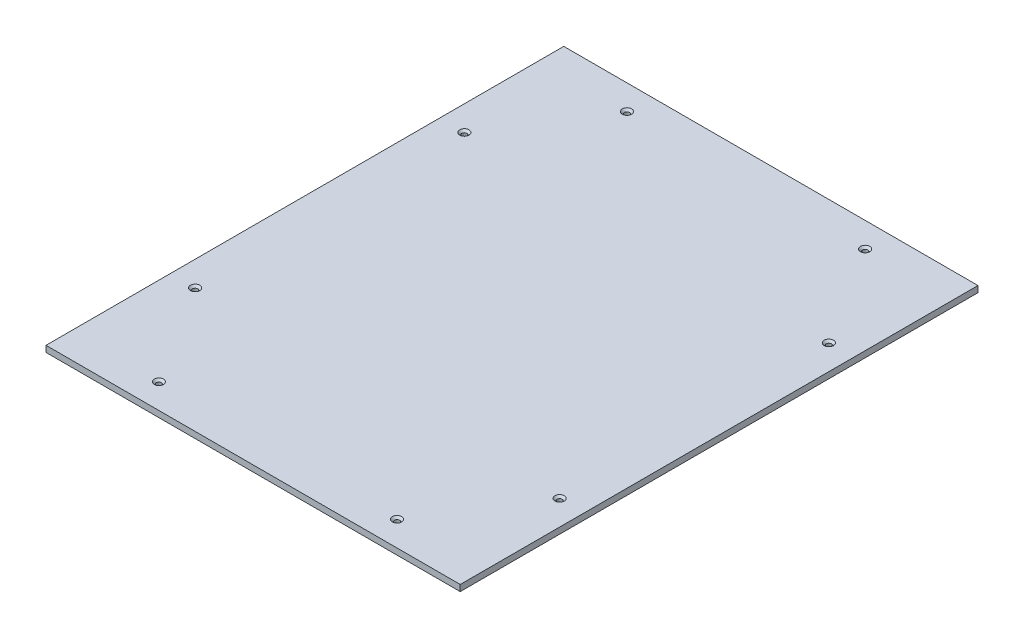
SolidWorks part; units mm, degrees
ref_plane "Plan de face" through (0, 0, 0) normal (0, 0, 1) x (1, 0, 0)
ref_plane "Plan de dessus" through (0, 0, 0) normal (0, 1, 0) x (1, 0, 0)
ref_plane "Plan de droite" through (0, 0, 0) normal (1, 0, 0) x (0, 0, -1)
sketch "Esquisse1" plane through (0, 0, 0) normal (0, 1, 0) x (1, 0, 0)
  line L1 (-200, -250) -> (200, -250)
  line L2 (-200, -250) -> (-200, 250)
  line L3 (-200, 250) -> (200, 250)
  line L4 (200, -250) -> (200, 250)
  line L5 (-200, -250) -> (200, 250) construction
  line L6 (-200, 250) -> (200, -250) construction
  point P0 (0, 0)
  dimension "D1" = 400
  dimension "D2" = 500
extrude "Boss.-Extru.1" add sketch "Esquisse1" along normal blind 6
sketch "Esquisse2" plane through (0, 6, 0) normal (0, 1, 0) x (1, 0, 0)
  line L0 (-200, 250) -> (-200, -250) construction
  line L1 (-176, -226) -> (176, -226) construction
  line L2 (-176, -226) -> (-176, 226) construction
  line L3 (-176, 226) -> (176, 226) construction
  line L4 (176, -226) -> (176, 226) construction
  line L5 (-176, -226) -> (176, 226) construction
  line L6 (-176, 226) -> (176, -226) construction
  line L7 (200, 250) -> (-200, 250) construction
  line L8 (-176, 0) -> (176, 0) construction
  line L9 (0, 226) -> (0, -226) construction
  circle A0 centre (-176, 130) radius 2.5
  circle A1 centre (176, 130) radius 2.5
  circle A2 centre (-176, -130) radius 2.5
  circle A3 centre (176, -130) radius 2.5
  circle A4 centre (-115, 226) radius 2.5
  circle A5 centre (115, 226) radius 2.5
  circle A6 centre (-115, -226) radius 2.5
  circle A7 centre (115, -226) radius 2.5
  point P0 (0, 0)
  dimension "D3" = 5
  dimension "D1" = 24
  dimension "D2" = 24
  dimension "D4" = 230
  dimension "D5" = 260
extrude "Enlèv. mat.-Extru.1" cut sketch "Esquisse2" against normal through all
chamfer "Chanfrein1" distance 2 angle 45 8 edges at (-176, 6, -127.5) (-115, 6, -223.5) (115, 6, -223.5) (176, 6, -127.5) (176, 6, 132.5) (115, 6, 228.5) (-115, 6, 228.5) (-176, 6, 132.5)
chamfer "Chanfrein2" [suppressed] distance 2 angle 45
